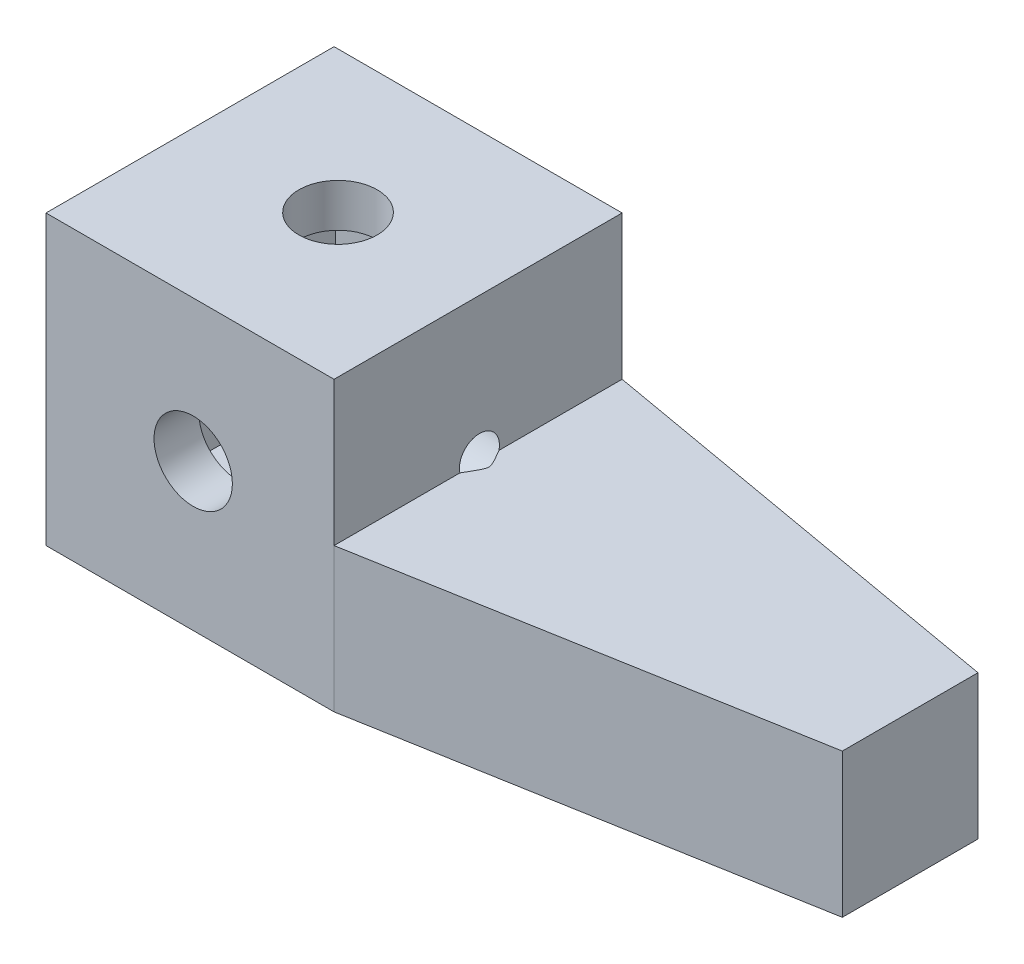
SolidWorks part; units mm, degrees
ref_plane "Front Plane" through (0, 0, 0) normal (0, 0, 1) x (1, 0, 0)
ref_plane "Top Plane" through (0, 0, 0) normal (0, 1, 0) x (1, 0, 0)
ref_plane "Right Plane" through (0, 0, 0) normal (1, 0, 0) x (0, 0, -1)
sketch "Sketch1" plane through (0, 0, 0) normal (0, 1, 0) x (1, 0, 0)
  line L0 (0, 0) -> (19.05, 3.359)
  line L1 (19.05, 3.359) -> (19.05, 9.341)
  line L2 (19.05, 9.341) -> (0, 12.7)
  line L3 (0, 12.7) -> (0, 0)
  dimension "D1" = 19.05
  dimension "D2" = 100
  dimension "D3" = 12.7
  dimension "D4" = 100
extrude "Boss-Extrude1" add sketch "Sketch1" along normal blind 6.35
sketch "Sketch2" plane through (0, 0, 0) normal (0, 1, 0) x (1, 0, 0)
  line L0 (0, 0) -> (-12.7, 0)
  line L1 (-12.7, 0) -> (-12.7, 12.7)
  line L2 (-12.7, 12.7) -> (0, 12.7)
  line L3 (0, 12.7) -> (0, 0)
extrude "Boss-Extrude2" add sketch "Sketch2" along normal blind 12.7
sketch "Sketch3" plane through (0, 0, 0) normal (0, 1, 0) x (1, 0, 0)
  line L0 (-1.905, 1.9763) -> (-1.905, 10.8663)
  line L1 (-1.905, 10.8663) -> (-10.795, 10.8663)
  line L2 (-10.795, 10.8663) -> (-10.795, 1.9763)
  line L3 (-10.795, 1.9763) -> (-1.905, 1.9763)
  dimension "D1" = 1.905
  dimension "D2" = 1.9763
  dimension "D3" = 8.89
extrude "Cut-Extrude1" cut sketch "Sketch3" against normal blind 4.445 and the other way blind 4.445 from offset 6.35
hole_wizard "#8-32 Tapped Hole1" positions "Sketch14" profile "Sketch7" tap size "#8-32" standard "ANSI Inch"
sketch "Sketch14" plane through (0, 0, 0) normal (0, 0, 1) x (1, 0, 0)
  point P0 (-6.2101, 6.468)
  point P2 (-17.7914, 4.5631)
  point P4 (-6.2101, 6.468)
sketch "Sketch7" plane through (-6.2101, 6.468, 0) normal (1, 0, 0) x (0, -1, 0)
  line L0 (0, 0) -> (0, 13.3212)
  line L1 (0, 13.3212) -> (1.7272, 12.2834)
  line L2 (1.7272, 12.2834) -> (1.7272, 0)
  line L5 (1.7272, 0) -> (0, 0)
  line L10 (0, 13.3212) -> (-1.7272, 12.2834) construction
  line L11 (0, -6.35) -> (0, 107.95) construction
  dimension "Tap Drill Dia." = 3.4544
  dimension "Tap Drill Depth" = 12.2834
  dimension "Drill Angle" = 118
cosmetic thread "Hole Thread1" parameters "D1"=9.906, "D2"=4.1656
cosmetic thread "Hole Thread2" parameters "D1"=9.906, "D2"=4.1656
hole_wizard "#8-32 Tapped Hole2" positions "Sketch16" profile "Sketch15" tap size "#8-32" standard "ANSI Inch"
sketch "Sketch16" plane through (0, 0, -12.7) normal (0, 0, -1) x (-1, 0, 0)
  point P0 (6.2101, 6.468)
  point P3 (6.2101, 6.468)
sketch "Sketch15" plane through (-6.2101, 6.468, -12.7) normal (1, 0, 0) x (0, 1, 0)
  line L0 (0, 0) -> (0, 13.2298)
  line L1 (0, 13.2298) -> (1.7272, 12.192)
  line L2 (1.7272, 12.192) -> (1.7272, 0)
  line L5 (1.7272, 0) -> (0, 0)
  line L10 (0, 13.2298) -> (-1.7272, 12.192) construction
  line L11 (0, -6.35) -> (0, 107.95) construction
  dimension "Tap Drill Dia." = 3.4544
  dimension "Tap Drill Depth" = 12.192
  dimension "Drill Angle" = 118
cosmetic thread "Hole Thread3" parameters "D1"=1.8337, "D2"=4.1656
hole_wizard "#8-32 Tapped Hole3" positions "Sketch18" profile "Sketch17" tap size "#8-32" standard "ANSI Inch"
sketch "Sketch18" plane through (0, 12.7, 0) normal (0, 1, 0) x (1, 0, 0)
  point P0 (-6.2849, 6.4606)
sketch "Sketch17" plane through (-6.2849, 12.7, -6.4606) normal (1, 0, 0) x (0, 0, 1)
  line L0 (0, 0) -> (0, 13.2298)
  line L1 (0, 13.2298) -> (1.7272, 12.192)
  line L2 (1.7272, 12.192) -> (1.7272, 0)
  line L5 (1.7272, 0) -> (0, 0)
  line L10 (0, 13.2298) -> (-1.7272, 12.192) construction
  line L11 (0, -6.35) -> (0, 107.95) construction
  dimension "Tap Drill Dia." = 3.4544
  dimension "Tap Drill Depth" = 12.192
  dimension "Drill Angle" = 118
cosmetic thread "Hole Thread5" parameters "D1"=9.906, "D2"=4.1656
hole_wizard "#8-32 Tapped Hole4" positions "Sketch20" profile "Sketch19" tap size "#8-32" standard "ANSI Inch"
sketch "Sketch20" plane through (-12.7, 0, 0) normal (-1, 0, 0) x (0, 0, 1)
  point P0 (-6.4098, 6.5412)
sketch "Sketch19" plane through (-12.7, 6.5412, -6.4098) normal (0, 1, 0) x (0, 0, 1)
  line L0 (0, 0) -> (0, 13.2298)
  line L1 (0, 13.2298) -> (1.7272, 12.192)
  line L2 (1.7272, 12.192) -> (1.7272, 0)
  line L5 (1.7272, 0) -> (0, 0)
  line L10 (0, 13.2298) -> (-1.7272, 12.192) construction
  line L11 (0, -6.35) -> (0, 107.95) construction
  dimension "Tap Drill Dia." = 3.4544
  dimension "Tap Drill Depth" = 12.192
  dimension "Drill Angle" = 118
cosmetic thread "Hole Thread6" parameters "D1"=9.906, "D2"=4.1656
